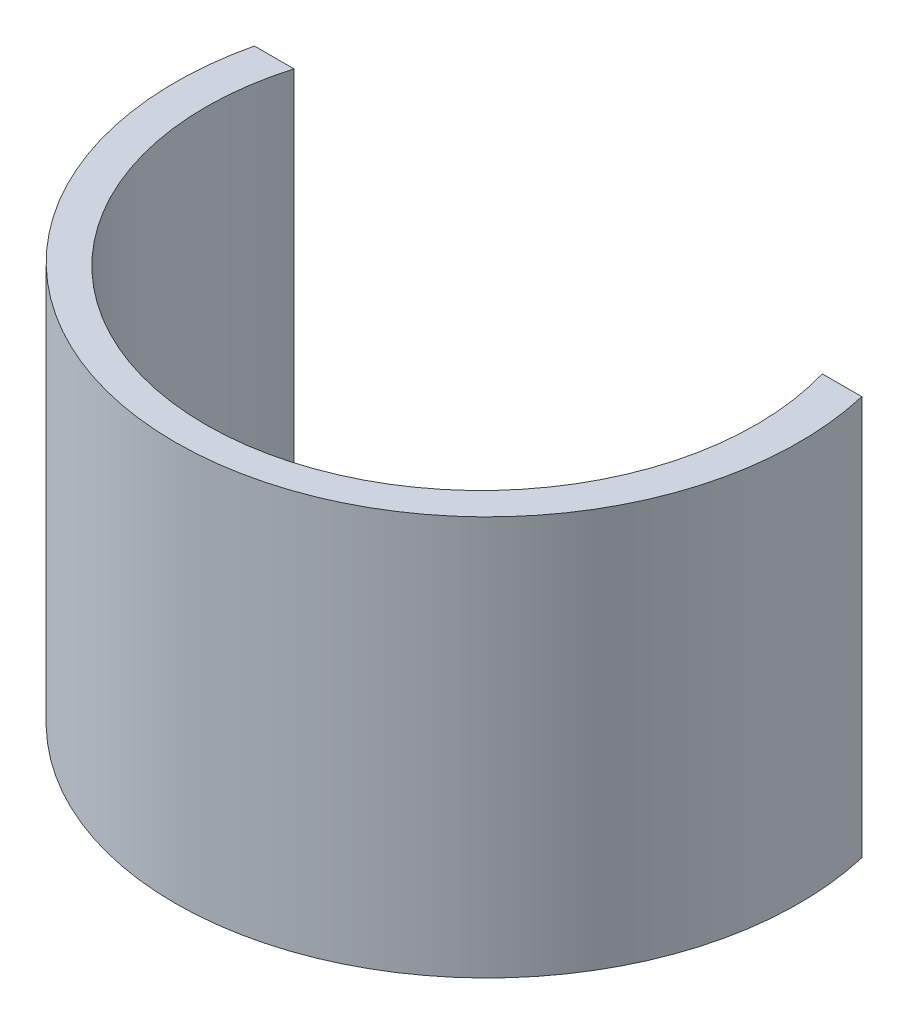
SolidWorks part; units mm, degrees
ref_plane "Front Plane" through (0, 0, 0) normal (0, 0, 1) x (1, 0, 0)
ref_plane "Top Plane" through (0, 0, 0) normal (0, 1, 0) x (1, 0, 0)
ref_plane "Right Plane" through (0, 0, 0) normal (1, 0, 0) x (0, 0, -1)
sketch "Sketch1" plane through (0, 0, 0) normal (0, 1, 0) x (1, 0, 0)
  line L0 (-1000, 0) -> (-104.805, 0) construction
  line L1 (0, -1000) -> (0, 49000) construction
  line L2 (91.805, -10) -> (90.2527, -10)
  line L3 (-76.805, 0) -> (76.805, 0)
  line L7 (-91.805, -10) -> (-90.2527, -10)
  line L9 (104.805, 0) -> (49000, 0) construction
  line L10 (-76.805, 0) -> (-76.805, 20)
  line L12 (-76.805, 0) -> (76.805, 0) construction
  line L13 (91.805, 20) -> (91.805, -10)
  line L14 (76.805, 20) -> (91.805, 20)
  line L17 (-76.805, 20) -> (-91.805, 20)
  line L18 (76.805, 0) -> (76.805, 20)
  line L19 (-91.805, 20) -> (-91.805, -10)
  arc A0 (-90.2527, -10) -> (90.2527, -10) centre (0, 0) ccw
  arc A1 (-76.805, 0) -> (76.805, 0) centre (0, 0) ccw
  dimension "D1" = 181.61
  dimension "D2" = 14
  dimension "D3" = 30
  dimension "D4" = 15
ref_plane "Plane5" through (0, 0, 0) normal (0, 1, 0) x (1, 0, 0)
sketch "Sketch40" plane through (0, 0, 0) normal (0, 1, 0) x (1, 0, 0)
  line L0 (76.805, 20) -> (66.805, 20)
  line L1 (0, 0) -> (0, 14.7735)
  line L2 (-76.805, 20) -> (-66.805, 20)
  arc A0 (76.805, 20) -> (-76.805, 20) centre (0, 2.066) cw
  arc A1 (66.805, 20) -> (-66.805, 20) centre (0, 0.4959) cw
  dimension "D1" = 10
extrude "Boss-Extrude5" add sketch "Sketch40" along normal blind 70 and the other way blind 31 contours L0 A1 L2 A0
